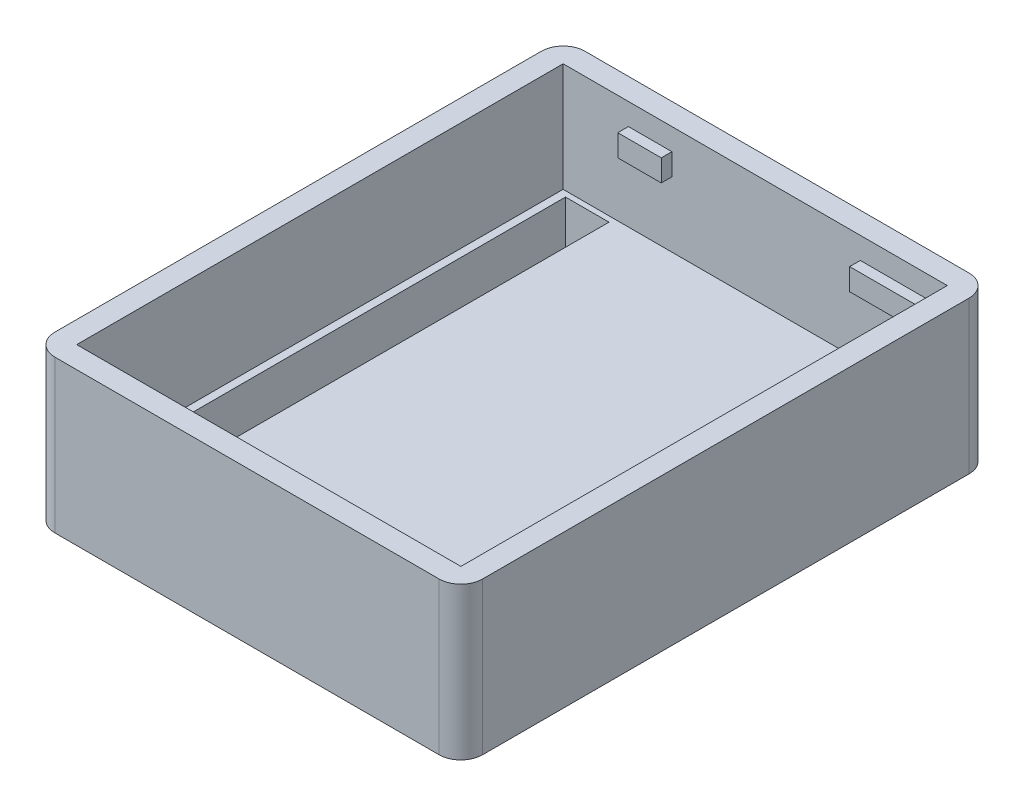
SolidWorks part; units mm, degrees
ref_plane "Plan de face" through (0, 0, 0) normal (0, 0, 1) x (1, 0, 0)
ref_plane "Plan de dessus" through (0, 0, 0) normal (0, 1, 0) x (1, 0, 0)
ref_plane "Plan de droite" through (0, 0, 0) normal (1, 0, 0) x (0, 0, -1)
sketch "Esquisse1" plane through (0, 0, 0) normal (0, 1, 0) x (1, 0, 0)
  line L1 (1, 0) -> (18.6601, 0)
  line L2 (0, 1) -> (0, 23.3619)
  line L3 (1, 24.3619) -> (18.6601, 24.3619)
  line L4 (19.6601, 1) -> (19.6601, 23.3619)
  arc A0 (18.6601, 0) -> (19.6601, 1) centre (18.6601, 1) ccw
  arc A1 (18.6601, 24.3619) -> (19.6601, 23.3619) centre (18.6601, 23.3619) cw
  arc A2 (0, 23.3619) -> (1, 24.3619) centre (1, 23.3619) cw
  arc A3 (1, 0) -> (0, 1) centre (1, 1) cw
  point P7 (19.6601, 0)
  point P12 (0, 24.3619)
  point P15 (0, 0)
  dimension "D3" = 1
  dimension "D1" = 24.3619
  dimension "D2" = 19.6601
extrude "Boss.-Extru.1" add sketch "Esquisse1" along normal blind 7 contours L1 A0 L4 A1 L3 A2 L2 A3
sketch "Esquisse2" plane through (0, 7, 0) normal (0, 1, 0) x (1, 0, 0)
  line L8 (1, 1) -> (18.6601, 1)
  line L9 (18.6601, 1) -> (18.6601, 23.3619)
  line L10 (18.6601, 23.3619) -> (1, 23.3619)
  line L11 (1, 23.3619) -> (1, 1)
  line L12 (1, 1) -> (18.6601, 1)
  line L13 (18.6601, 1) -> (18.6601, 23.3619)
  line L14 (18.6601, 23.3619) -> (1, 23.3619)
  line L15 (1, 23.3619) -> (1, 1)
  dimension "D1" = 1
extrude "Enlèv. mat.-Extru.1" cut sketch "Esquisse2" against normal blind 5
sketch "Esquisse5" plane through (0, 2, 0) normal (0, 1, 0) x (1, 0, 0)
  line L0 (1, 1) -> (18.6601, 1) construction
  line L1 (3.36, 23.11) -> (1.36, 23.11)
  line L2 (3.36, 23.11) -> (3.36, 1.25)
  line L3 (3.36, 1.25) -> (1.36, 1.25)
  line L4 (1.36, 23.11) -> (1.36, 1.25)
  line L5 (1, 23.3619) -> (1, 1) construction
  dimension "D1" = 21.86
  dimension "D2" = 2
  dimension "D3" = 0.25
  dimension "D4" = 0.36
extrude "Enlèv. mat.-Extru.3" cut sketch "Esquisse5" against normal through all
sketch "Esquisse6" plane through (0, 0, -23.3619) normal (0, 0, 1) x (1, 0, 0)
  line L0 (18.6601, 2) -> (18.6601, 7) construction
  line L1 (17.6601, 5) -> (14.6601, 5)
  line L2 (17.6601, 5) -> (17.6601, 6)
  line L3 (17.6601, 6) -> (14.6601, 6)
  line L4 (14.6601, 5) -> (14.6601, 6)
  line L5 (18.6601, 2) -> (1, 2) construction
  dimension "D1" = 3
  dimension "D2" = 1
  dimension "D3" = 1
  dimension "D4" = 3
extrude "Boss.-Extru.2" add sketch "Esquisse6" along normal blind 0.489
sketch "Esquisse7" plane through (18.6601, 0, 0) normal (-1, 0, 0) x (0, 0, 1)
  line L0 (-23.3619, 2) -> (-23.3619, 7) construction
  line L1 (-22.3619, 5) -> (-19.3619, 5)
  line L2 (-22.3619, 5) -> (-22.3619, 6)
  line L3 (-22.3619, 6) -> (-19.3619, 6)
  line L4 (-19.3619, 5) -> (-19.3619, 6)
  line L5 (-1, 2) -> (-23.3619, 2) construction
  dimension "D1" = 3
  dimension "D2" = 1
  dimension "D3" = 1
  dimension "D4" = 3
extrude "Boss.-Extru.3" add sketch "Esquisse7" along normal blind 0.489
sketch "Esquisse8" plane through (0, 0, -1) normal (0, 0, -1) x (-1, 0, 0)
  line L0 (-18.6601, 2) -> (-18.6601, 7) construction
  line L1 (-17.6601, 6) -> (-14.6601, 6)
  line L2 (-17.6601, 6) -> (-17.6601, 5)
  line L3 (-17.6601, 5) -> (-14.6601, 5)
  line L4 (-14.6601, 6) -> (-14.6601, 5)
  line L5 (-1, 2) -> (-18.6601, 2) construction
  dimension "D1" = 3
  dimension "D2" = 1
  dimension "D3" = 1
  dimension "D4" = 3
extrude "Boss.-Extru.4" add sketch "Esquisse8" along normal blind 0.489
sketch "Esquisse9" plane through (18.6601, 0, 0) normal (-1, 0, 0) x (0, 0, 1)
  line L0 (-1, 2) -> (-23.3619, 2) construction
  line L1 (-2, 6) -> (-5, 6)
  line L2 (-2, 6) -> (-2, 5)
  line L3 (-2, 5) -> (-5, 5)
  line L4 (-5, 6) -> (-5, 5)
  line L5 (-1, 2) -> (-1, 7) construction
  dimension "D1" = 3
  dimension "D2" = 1
  dimension "D3" = 3
  dimension "D4" = 1
extrude "Boss.-Extru.5" add sketch "Esquisse9" along normal blind 0.489
sketch "Esquisse10" plane through (0, 0, -23.3619) normal (0, 0, 1) x (1, 0, 0)
  line L0 (1, 2) -> (1, 7) construction
  line L1 (4, 5) -> (6, 5)
  line L2 (4, 5) -> (4, 6)
  line L3 (4, 6) -> (6, 6)
  line L4 (6, 5) -> (6, 6)
  line L5 (18.6601, 2) -> (1, 2) construction
  dimension "D1" = 2
  dimension "D2" = 1
  dimension "D3" = 3
  dimension "D4" = 3
extrude "Boss.-Extru.6" add sketch "Esquisse10" along normal blind 0.489
sketch "Esquisse11" plane through (0, 0, -1) normal (0, 0, -1) x (-1, 0, 0)
  line L0 (-1, 2) -> (-18.6601, 2) construction
  line L1 (-4, 6) -> (-6, 6)
  line L2 (-4, 6) -> (-4, 5)
  line L3 (-4, 5) -> (-6, 5)
  line L4 (-6, 6) -> (-6, 5)
  line L5 (-1, 2) -> (-1, 7) construction
  dimension "D1" = 2
  dimension "D2" = 1
  dimension "D3" = 3
  dimension "D4" = 3
extrude "Boss.-Extru.7" add sketch "Esquisse11" along normal blind 0.489
